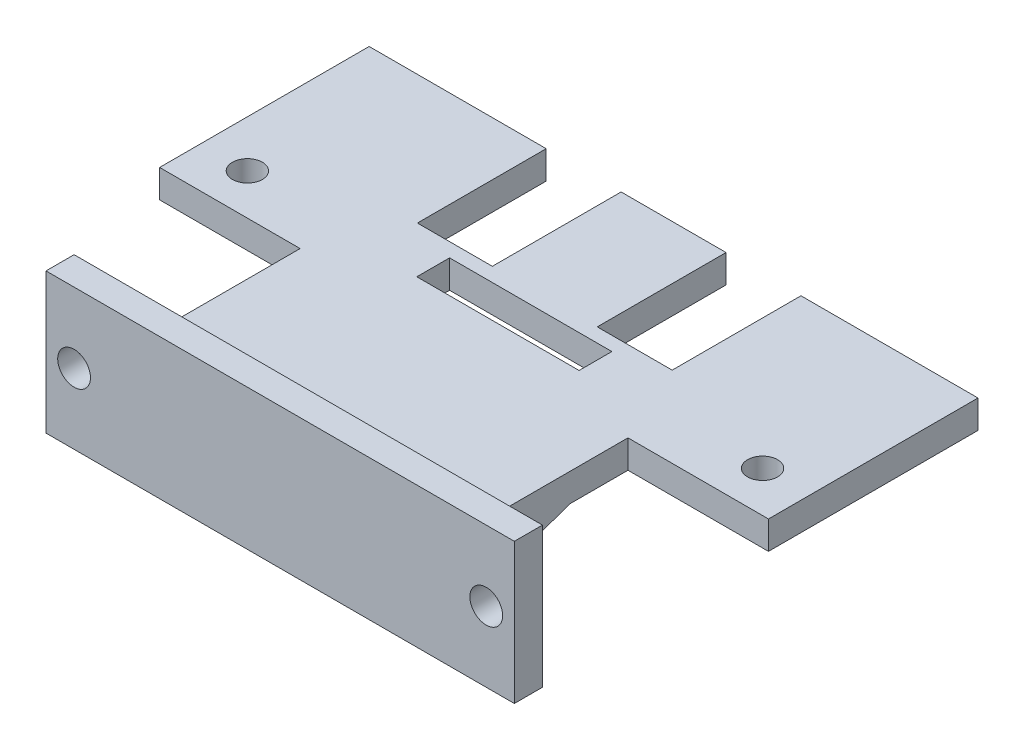
SolidWorks part; units mm, degrees
ref_plane "Front Plane" through (0, 0, 0) normal (0, 0, 1) x (1, 0, 0)
ref_plane "Top Plane" through (0, 0, 0) normal (0, 1, 0) x (1, 0, 0)
ref_plane "Right Plane" through (0, 0, 0) normal (1, 0, 0) x (0, 0, -1)
ref_plane "Plane1" through (0, 0, 25) normal (0, 0, 1) x (1, 0, 0)
sketch "Sketch1" plane through (0, 0, 25) normal (0, 0, 1) x (1, 0, 0)
  line L0 (25, 7) -> (-25, 7)
  line L1 (-25, 7) -> (-25, -8)
  line L2 (-25, -8) -> (25, -8)
  line L3 (25, -8) -> (25, 7)
extrude "Boss-Extrude1" add sketch "Sketch1" against normal blind 3
sketch "Sketch2" plane through (0, 0, 22) normal (0, 0, -1) x (-1, 0, 0)
  line L0 (17.5, 3) -> (17.5, 0)
  line L1 (17.5, 0) -> (-17.5, 0)
  line L2 (-17.5, 0) -> (-17.5, 3)
  line L3 (-17.5, 3) -> (17.5, 3)
extrude "Boss-Extrude2" add sketch "Sketch2" along normal blind 47
sketch "Sketch3" plane through (17.5, 0, 0) normal (1, 0, 0) x (0, 0, -1)
  line L0 (25, 0) -> (-5.3692, 0)
  line L1 (-5.3692, 0) -> (-5.3692, 3)
  line L2 (-5.3692, 3) -> (25, 3)
  line L3 (25, 3) -> (25, 0)
extrude "Boss-Extrude3" add sketch "Sketch3" along normal blind 15
sketch "Sketch4" plane through (-17.5, 0, 0) normal (-1, 0, 0) x (0, 0, 1)
  line L0 (5.3692, 0) -> (-25, 0)
  line L1 (-25, 0) -> (-25, 3)
  line L2 (-25, 3) -> (5.3692, 3)
  line L3 (5.3692, 3) -> (5.3692, 0)
extrude "Boss-Extrude4" add sketch "Sketch4" along normal blind 15
sketch "Sketch5" plane through (0, 0, 0) normal (0, -1, 0) x (1, 0, 0)
  line L0 (17.5, -25) -> (17.5, -17)
  line L1 (17.5, -17) -> (13.6, -17)
  line L2 (13.6, -17) -> (13.6, -3.25)
  line L3 (13.6, -3.25) -> (5.6, -3.25)
  line L4 (5.6, -3.25) -> (5.6, -17)
  line L5 (5.6, -17) -> (-5.6, -17)
  line L6 (-5.6, -17) -> (-5.6, -3.25)
  line L7 (-5.6, -3.25) -> (-13.6, -3.25)
  line L8 (-13.6, -3.25) -> (-13.6, -17)
  line L9 (-13.6, -17) -> (-17.5, -17)
  line L10 (-17.5, -17) -> (-17.5, -25)
  line L11 (-17.5, -25) -> (17.5, -25)
extrude "Cut-Extrude1" cut sketch "Sketch5" against normal through all
hole_wizard "Ø4.0 (4) Diameter Hole1" positions "Sketch7" profile "Sketch6" hole size "Ø4.0" standard "ANSI Metric"
sketch "Sketch7" plane through (0, 0, 25) normal (0, 0, 1) x (1, 0, 0)
  point P0 (22, -0.5)
  point P1 (-22, -0.5)
sketch "Sketch6" plane through (22, -0.5, 25) normal (1, 0, 0) x (0, -1, 0)
  line L0 (0, 0) -> (0, 3)
  line L1 (0, 3) -> (1.75, 3)
  line L2 (1.75, 3) -> (1.75, 0)
  line L5 (1.75, 0) -> (0, 0)
  line L11 (0, -6.35) -> (0, 107.95) construction
  dimension "Thru Hole Dia." = 3.5
  dimension "Thru Hole Depth" = 3
hole_wizard "Ø3.2 (3.2) Diameter Hole1" positions "Sketch9" profile "Sketch8" hole size "Ø3.2" standard "ANSI Metric"
sketch "Sketch9" plane through (0, 3, 0) normal (0, 1, 0) x (1, 0, 0)
  point P0 (-27.5, -1)
  point P1 (27.5, -1)
sketch "Sketch8" plane through (-27.5, 3, 1) normal (1, 0, 0) x (0, 0, 1)
  line L0 (0, 0) -> (0, 11)
  line L1 (0, 11) -> (1.6, 11)
  line L2 (1.6, 11) -> (1.6, 0)
  line L5 (1.6, 0) -> (0, 0)
  line L11 (0, -6.35) -> (0, 107.95) construction
  dimension "Thru Hole Dia." = 3.2
  dimension "Thru Hole Depth" = 11
sketch "Sketch14" plane through (-17.5, 0, 0) normal (1, 0, 0) x (0, 0, -1)
  line L1 (25, 0) -> (17, 0)
  line L2 (25, 0) -> (25, 3)
  line L3 (25, 3) -> (17, 3)
  line L4 (17, 0) -> (17, 3)
  line L5 (21, 3) -> (21, 0) construction
  line L6 (25, 1.5) -> (17, 1.5) construction
  point P56 (21, 1.5)
  dimension "D1" = 3
  dimension "D2" = 8
extrude "Cut-Extrude2" cut sketch "Sketch14" along normal through all from surface at -15 starting at face at (-32.5, 1.5, -9.8154)
sketch "Sketch15" plane through (0, 3, 0) normal (0, 1, 0) x (1, 0, 0)
  line L1 (-8.6637, 1.75) -> (8.6637, 1.75)
  line L2 (-8.6637, 1.75) -> (-8.6637, -1.75)
  line L3 (-8.6637, -1.75) -> (8.6637, -1.75)
  line L4 (8.6637, 1.75) -> (8.6637, -1.75)
  line L5 (-8.6637, 1.75) -> (8.6637, -1.75) construction
  line L6 (-8.6637, -1.75) -> (8.6637, 1.75) construction
  point P0 (0, 0)
  dimension "D1" = 3.5
extrude "Cut-Extrude3" cut sketch "Sketch15" against normal blind 10
sketch "Sketch17" plane through (17.5, 0, 0) normal (1, 0, 0) x (0, 0, -1)
  line L0 (-22, -3.656) -> (-11.5401, 0)
  line L3 (-22, -8) -> (-22, 7) construction
  line L4 (-5.3692, 0) -> (-22, 0) construction
  line L5 (-22, -3.656) -> (-22, 0)
  line L6 (-22, 0) -> (-11.5401, 0)
extrude "Boss-Extrude5" add sketch "Sketch17" against normal blind 5
mirror "Mirror1" about plane through (0, 0, 0) normal (1, 0, 0) of "Boss-Extrude5"
